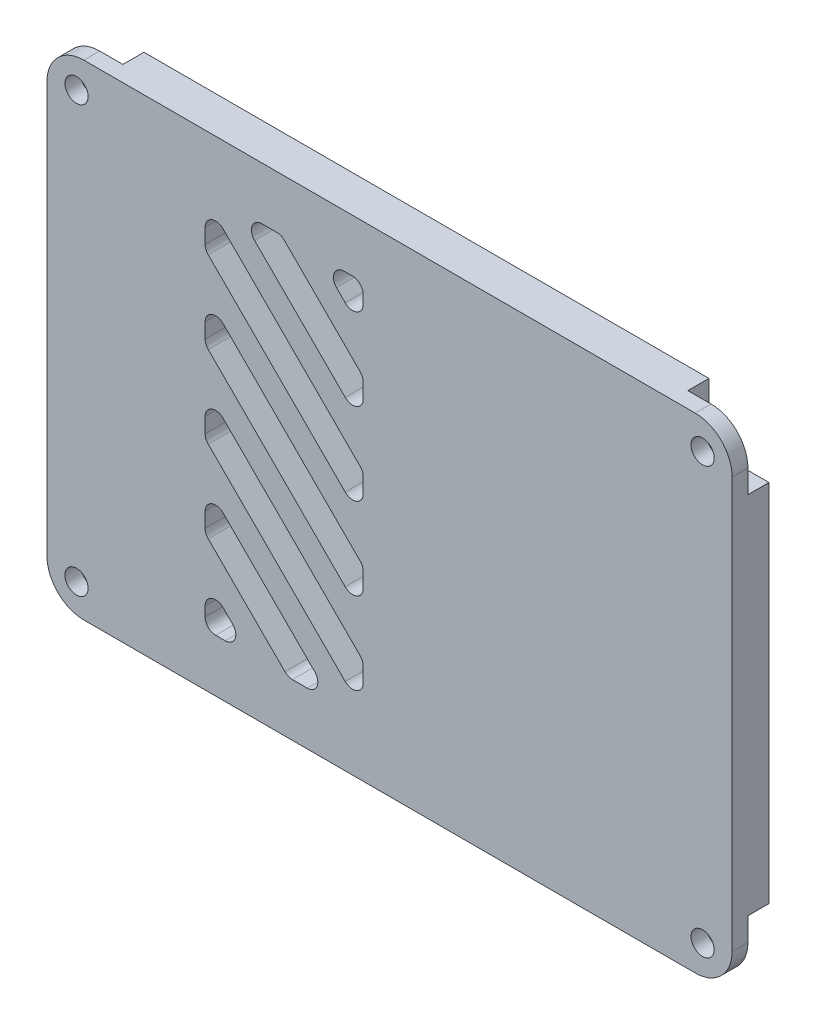
SolidWorks part; units mm, degrees
ref_plane "Front Plane" through (0, 0, 0) normal (0, 0, 1) x (1, 0, 0)
ref_plane "Top Plane" through (0, 0, 0) normal (0, 1, 0) x (1, 0, 0)
ref_plane "Right Plane" through (0, 0, 0) normal (1, 0, 0) x (0, 0, -1)
sketch "Sketch1" plane through (0, 0, 0) normal (0, 0, 1) x (1, 0, 0)
  line L1 (3.5, 23) -> (61.5, 23)
  line L2 (0, 19.5) -> (0, -19.5)
  line L3 (3.5, -23) -> (61.5, -23)
  line L4 (65, 19.5) -> (65, -19.5)
  arc A0 (61.5, -23) -> (65, -19.5) centre (61.5, -19.5) ccw
  arc A1 (0, -19.5) -> (3.5, -23) centre (3.5, -19.5) ccw
  arc A2 (61.5, 23) -> (65, 19.5) centre (61.5, 19.5) cw
  arc A3 (3.5, 23) -> (0, 19.5) centre (3.5, 19.5) ccw
  point P4 (0, 0)
  point P8 (65, -23)
  point P13 (65, 23)
  point P16 (0, 23)
  dimension "D3" = 3.5
  dimension "D1" = 65
  dimension "D2" = 46
extrude "Boss-Extrude1" add sketch "Sketch1" along normal blind 3.5 contours L2 A1 L3 A0 L4 A2 L1 A3
sketch "Sketch2" plane through (0, 0, 3.5) normal (0, 0, 1) x (1, 0, 0)
  arc A0 (1.721, -20.4138) -> (2.5862, -21.279) centre (2.8, -20.2) ccw construction
  arc A1 (2.5862, -21.279) -> (1.721, -20.4138) centre (2.8, -20.2) ccw construction
  arc A2 (1.721, -20.4138) -> (2.5862, -21.279) centre (2.8, -20.2) ccw
  arc A3 (2.5862, -21.279) -> (1.721, -20.4138) centre (2.8, -20.2) ccw
  arc A4 (2.5862, 21.279) -> (1.721, 20.4138) centre (2.8, 20.2) ccw construction
  arc A5 (3.5, 21.0485) -> (2.5862, 21.279) centre (2.8, 20.2) ccw construction
  arc A6 (3.5, 19.3515) -> (3.5, 21.0485) centre (2.8, 20.2) ccw construction
  arc A7 (1.721, 20.4138) -> (3.5, 19.3515) centre (2.8, 20.2) ccw construction
  arc A8 (2.5862, 21.279) -> (1.721, 20.4138) centre (2.8, 20.2) ccw
  arc A9 (3.5, 21.0485) -> (2.5862, 21.279) centre (2.8, 20.2) ccw
  arc A10 (3.5, 19.3515) -> (3.5, 21.0485) centre (2.8, 20.2) ccw
  arc A11 (1.721, 20.4138) -> (3.5, 19.3515) centre (2.8, 20.2) ccw
  arc A12 (62.4138, -21.279) -> (63.279, -20.4138) centre (62.2, -20.2) ccw construction
  arc A13 (63.279, -20.4138) -> (62.4138, -21.279) centre (62.2, -20.2) ccw construction
  arc A14 (62.4138, -21.279) -> (63.279, -20.4138) centre (62.2, -20.2) ccw
  arc A15 (63.279, -20.4138) -> (62.4138, -21.279) centre (62.2, -20.2) ccw
  arc A16 (63.279, 20.4138) -> (62.4138, 21.279) centre (62.2, 20.2) ccw construction
  arc A17 (62.4138, 21.279) -> (63.279, 20.4138) centre (62.2, 20.2) ccw construction
  arc A18 (63.279, 20.4138) -> (62.4138, 21.279) centre (62.2, 20.2) ccw
  arc A19 (62.4138, 21.279) -> (63.279, 20.4138) centre (62.2, 20.2) ccw
extrude "Cut-Extrude1" cut sketch "Sketch2" against normal blind 10
sketch "Sketch3" plane through (0, 0, 0) normal (0, 0, -1) x (-1, 0, 0)
  line L0 (-2.8, -17.3) -> (0, -17.3)
  line L1 (0, 19.5) -> (0, -19.5) construction
  line L2 (-5.7, -23) -> (-5.7, -20.2)
  line L3 (-3.5, -23) -> (-61.5, -23) construction
  line L4 (-2.8, 17.3) -> (0, 17.3)
  line L5 (-5.7, 20.2) -> (-5.7, 23)
  line L6 (-3.5, 23) -> (-61.5, 23) construction
  line L7 (-59.3, 20.2) -> (-59.3, 23)
  line L8 (-62.2, 17.3) -> (-65, 17.3)
  line L9 (-65, 19.5) -> (-65, -19.5) construction
  line L10 (-62.2, -17.3) -> (-65, -17.3)
  line L11 (-59.3, -20.2) -> (-59.3, -23)
  line L12 (0, 19.5) -> (0, 17.3)
  line L13 (-3.5, 23) -> (-5.7, 23)
  line L14 (-59.3, 23) -> (-61.5, 23)
  line L15 (-65, 19.5) -> (-65, 17.3)
  line L16 (-65, -17.3) -> (-65, -19.5)
  line L17 (-59.3, -23) -> (-61.5, -23)
  line L18 (-3.5, -23) -> (-5.7, -23)
  line L19 (0, -17.3) -> (0, -19.5)
  circle A0 centre (-2.8, 20.2) radius 2.9 construction
  circle A1 centre (-2.8, -20.2) radius 2.9 construction
  circle A2 centre (-62.2, 20.2) radius 2.9 construction
  circle A3 centre (-62.2, -20.2) radius 2.9 construction
  arc A4 (-2.8, -17.3) -> (-5.7, -20.2) centre (-2.8, -20.2) ccw
  arc A5 (-5.7, 20.2) -> (-2.8, 17.3) centre (-2.8, 20.2) ccw
  arc A6 (-59.3, 20.2) -> (-62.2, 17.3) centre (-62.2, 20.2) cw
  arc A7 (-62.2, -17.3) -> (-59.3, -20.2) centre (-62.2, -20.2) cw
  arc A8 (-65, -19.5) -> (-61.5, -23) centre (-61.5, -19.5) ccw construction
  arc A9 (-65, -19.5) -> (-61.5, -23) centre (-61.5, -19.5) ccw
  arc A10 (-61.5, 23) -> (-65, 19.5) centre (-61.5, 19.5) ccw construction
  arc A11 (-61.5, 23) -> (-65, 19.5) centre (-61.5, 19.5) ccw
  arc A12 (0, 19.5) -> (-3.5, 23) centre (-3.5, 19.5) ccw construction
  arc A13 (0, 19.5) -> (-3.5, 23) centre (-3.5, 19.5) ccw
  arc A14 (-3.5, -23) -> (0, -19.5) centre (-3.5, -19.5) ccw construction
  arc A15 (-3.5, -23) -> (0, -19.5) centre (-3.5, -19.5) ccw
  dimension "D1" = 5.8
extrude "Cut-Extrude2" cut sketch "Sketch3" against normal blind 2
sketch "Sketch4" plane through (0, 0, 0) normal (0, 0, -1) x (-1, 0, 0)
  line L0 (0, 17.3) -> (0, -17.3) construction
  line L1 (-30, 18) -> (-15, 18)
  line L2 (-30, 18) -> (-30, -18)
  line L3 (-30, -18) -> (-15, -18)
  line L4 (-15, 18) -> (-15, -18)
  line L5 (-65, 17.3) -> (-65, -17.3) construction
  line L6 (-5.7, -23) -> (-59.3, -23) construction
  line L7 (-5.7, 23) -> (-59.3, 23) construction
  line L8 (-30, 13.7574) -> (-25.7574, 18)
  line L9 (-30, 10.2218) -> (-22.2218, 18)
  line L10 (-30, 5.9792) -> (-17.9792, 18)
  line L11 (-30, 2.4437) -> (-15, 17.4437)
  line L12 (-30, -1.799) -> (-15, 13.201)
  line L13 (-30, -5.3345) -> (-15, 9.6655)
  line L14 (-30, -9.5772) -> (-15, 5.4228)
  line L15 (-30, -13.1127) -> (-15, 1.8873)
  line L16 (-30, -17.3553) -> (-15, -2.3553)
  line L17 (-27.1091, -18) -> (-15, -5.8909)
  line L18 (-22.8665, -18) -> (-15, -10.1335)
  line L19 (-19.331, -18) -> (-15, -13.669)
  point P14 (-27.8787, 15.8787)
  dimension "D5" = 45
  dimension "D1" = 15
  dimension "D2" = 35
  dimension "D3" = 5
  dimension "D4" = 5
  dimension "D6" = 3
  dimension "D7" = 2.5
  dimension "D8" = 3
  dimension "D9" = 2.5
  dimension "D10" = 3
  dimension "D11" = 2.5
  dimension "D12" = 3
  dimension "D13" = 2.5
  dimension "D14" = 3
  dimension "D15" = 2.5
  dimension "D16" = 3
  dimension "D17" = 2.5
extrude "Cut-Extrude3" cut sketch "Sketch4" against normal blind 4
fillet "Fillet2" radius 1 26 edges at (30, 18, 1.75) (19.331, -18, 1.75) (15, -13.669, 1.75) (22.8665, -18, 1.75) (15, -10.1335, 1.75) (15, -5.8909, 1.75) (27.1091, -18, 1.75) (30, -17.3553, 1.75) (15, -2.3553, 1.75) (15, 1.8873, 1.75) (30, -13.1127, 1.75) (15, 5.4228, 1.75) (15, 9.6655, 1.75) (30, -9.5772, 1.75) (30, -5.3345, 1.75) (15, 13.201, 1.75) (15, 17.4437, 1.75) (30, -1.799, 1.75) (30, 2.4437, 1.75) (17.9792, 18, 1.75) (30, 5.9792, 1.75) (30, 10.2218, 1.75) (22.2218, 18, 1.75) (25.7574, 18, 1.75) (30, 13.7574, 1.75) (15, -18, 1.75)
